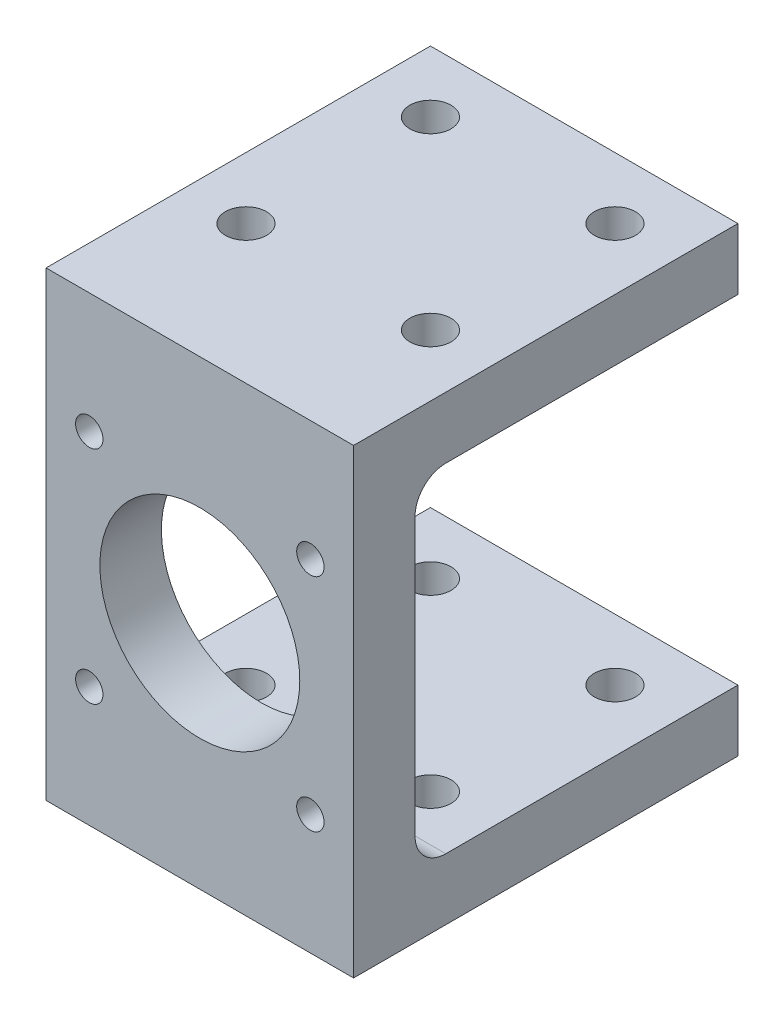
SolidWorks part; units mm, degrees
ref_plane "Front Plane" through (0, 0, 0) normal (0, 0, 1) x (1, 0, 0)
ref_plane "Top Plane" through (0, 0, 0) normal (0, 1, 0) x (1, 0, 0)
ref_plane "Right Plane" through (0, 0, 0) normal (1, 0, 0) x (0, 0, -1)
sketch "Sketch1" plane through (0, 0, 0) normal (0, 0, 1) x (1, 0, 0)
  line L1 (-12.7, -19.05) -> (12.7, -19.05)
  line L2 (-12.7, -19.05) -> (-12.7, 19.05)
  line L3 (-12.7, 19.05) -> (12.7, 19.05)
  line L4 (12.7, -19.05) -> (12.7, 19.05)
  line L5 (-12.7, -19.05) -> (12.7, 19.05) construction
  line L6 (-12.7, 19.05) -> (12.7, -19.05) construction
  line L7 (-9.1313, -9.1313) -> (9.1313, -9.1313) construction
  line L8 (-9.1313, -9.1313) -> (-9.1313, 9.1313) construction
  line L9 (-9.1313, 9.1313) -> (9.1313, 9.1313) construction
  line L10 (9.1313, -9.1313) -> (9.1313, 9.1313) construction
  line L11 (-9.1313, -9.1313) -> (9.1313, 9.1313) construction
  line L12 (-9.1313, 9.1313) -> (9.1313, -9.1313) construction
  circle A0 centre (0, 0) radius 8.255
  circle A1 centre (-9.1313, 9.1313) radius 1.1303
  circle A2 centre (9.1313, 9.1313) radius 1.1303
  circle A3 centre (-9.1313, -9.1313) radius 1.1303
  circle A4 centre (9.1313, -9.1313) radius 1.1303
  point P0 (0, 0)
  dimension "D3" = 16.51
  dimension "D5" = 2.2606
  dimension "D1" = 38.1
  dimension "D2" = 25.4
  dimension "D4" = 18.2626
  dimension "D6" = 18.2626
extrude "Boss-Extrude1" add sketch "Sketch1" against normal mid plane 31.75
sketch "Sketch3" plane through (12.7, 0, 0) normal (1, 0, 0) x (0, 0, -1)
  line L0 (15.875, -19.05) -> (15.875, 19.05) construction
  line L1 (15.875, 13.97) -> (-10.795, 13.97)
  line L2 (15.875, 13.97) -> (15.875, -13.97)
  line L3 (15.875, -13.97) -> (-10.795, -13.97)
  line L4 (-10.795, 13.97) -> (-10.795, -13.97)
  line L5 (15.875, 19.05) -> (-15.875, 19.05) construction
  line L6 (15.875, -19.05) -> (-15.875, -19.05) construction
  line L7 (-15.875, -19.05) -> (-15.875, 19.05) construction
  dimension "D1" = 5.08
  dimension "D2" = 5.08
  dimension "D3" = 5.08
extrude "Cut-Extrude1" cut sketch "Sketch3" against normal up to next
fillet "Fillet1" radius 2.54 2 edges at (0, -13.97, 10.795) (0, 13.97, 10.795)
sketch "Sketch5" plane through (0, 19.05, 0) normal (0, 1, 0) x (1, 0, 0)
  line L4 (-12.7, 15.875) -> (-12.7, -8.255)
  line L5 (-12.7, 15.875) -> (-12.7, -8.255)
  line L6 (12.7, -8.255) -> (12.7, 15.875)
  line L7 (12.7, 15.875) -> (-12.7, 15.875)
  line L8 (-12.7, -8.255) -> (12.7, -8.255)
  line L9 (-12.7, -8.255) -> (12.7, -8.255)
  line L10 (12.7, -8.255) -> (12.7, 15.875)
  line L11 (12.7, 15.875) -> (-12.7, 15.875)
  circle A0 centre (-7.62, 10.795) radius 1.7
  circle A1 centre (7.62, 10.795) radius 1.7
  circle A2 centre (7.62, -4.445) radius 1.7
  circle A3 centre (-7.62, -4.445) radius 1.7
  dimension "D2" = 3.4
  dimension "D3" = 5.08
  dimension "D4" = 5.08
  dimension "D5" = 5.08
  dimension "D6" = 3.81
  dimension "D1" = 0
extrude "Frame Mount Holes" cut sketch "Sketch5" against normal through all contours A0 | A3 | A2 | A1
